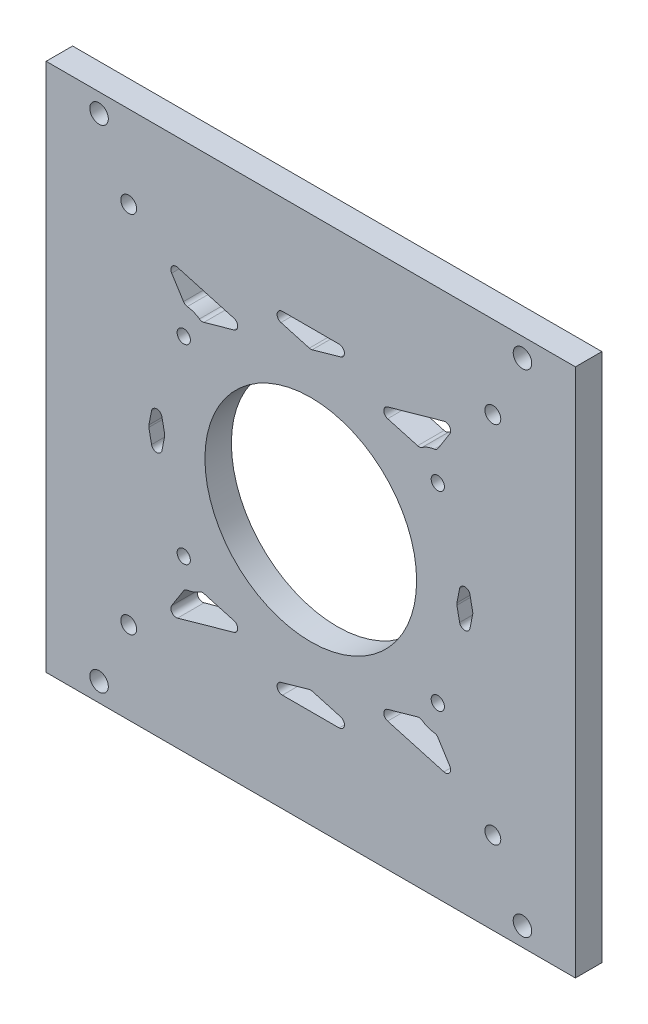
SolidWorks part; units mm, degrees
ref_plane "前视基准面" through (0, 0, 0) normal (0, 0, 1) x (1, 0, 0)
ref_plane "上视基准面" through (0, 0, 0) normal (0, 1, 0) x (1, 0, 0)
ref_plane "右视基准面" through (0, 0, 0) normal (1, 0, 0) x (0, 0, -1)
other "Configuration Table"
sketch "草图1" plane through (0, 0, 0) normal (0, 0, 1) x (1, 0, 0)
  line L1 (0, 0) -> (100, 0)
  line L2 (0, 0) -> (0, 100)
  line L3 (0, 100) -> (100, 100)
  line L4 (100, 0) -> (100, 100)
  line L5 (0, 0) -> (100, 100) construction
  line L6 (0, 100) -> (100, 0) construction
  point P4 (50, 50)
  dimension "D1" = 100
  dimension "D2" = 100
extrude "凸台-拉伸1" add sketch "草图1" along normal blind 5
sketch "草图2" plane through (0, 0, 5) normal (0, 0, 1) x (1, 0, 0)
  line L0 (28.3742, 96.45) -> (104.2073, 96.45) construction
  line L1 (0, 100) -> (100, 100)
  line L2 (0, 100) -> (0, 92.9)
  line L3 (0, 92.9) -> (100, 92.9)
  line L4 (0, 100) -> (0, 0)
  line L5 (0, 0) -> (100, 0)
  line L6 (100, 0) -> (100, 100)
  line L7 (100, 100) -> (0, 100)
  line L8 (0, 100) -> (0, 0)
  line L9 (0, 0) -> (100, 0)
  line L10 (100, 0) -> (100, 100)
  line L11 (100, 100) -> (0, 100)
  line L12 (100, 100) -> (100, 92.9)
  line L13 (0, 100) -> (100, 92.9) construction
  line L14 (0, 92.9) -> (100, 100) construction
  line L15 (0, 0) -> (100, 0)
  line L16 (0, 0) -> (0, 7.1)
  line L17 (0, 7.1) -> (100, 7.1)
  line L18 (100, 0) -> (100, 7.1)
  line L19 (0, 0) -> (100, 7.1) construction
  line L20 (0, 7.1) -> (100, 0) construction
  line L21 (5.1289, 3.55) -> (117.9259, 3.55) construction
  circle A0 centre (10, 96.45) radius 1.75
  circle A1 centre (90, 96.45) radius 1.75
  circle A2 centre (10, 3.55) radius 1.75
  circle A3 centre (90, 3.55) radius 1.75
  point P6 (50, 96.45)
  point P9 (50, 3.55)
  dimension "D4" = 3.5
  dimension "D5" = 3.5
  dimension "D6" = 3.5
  dimension "D7" = 3.5
  dimension "D2" = 7.1
  dimension "D3" = 7.1
  dimension "D8" = 10
  dimension "D9" = 10
  dimension "D10" = 10
  dimension "D11" = 10
  dimension "D1" = 0
extrude "切除-拉伸1" cut sketch "草图2" against normal blind 5 contours A0 | A1 | A2 | A3
sketch "草图3" plane through (0, 0, 5) normal (0, 0, 1) x (1, 0, 0)
  line L0 (100, 0) -> (100, 100) construction
  line L1 (0, 100) -> (100, 100) construction
  line L2 (0, 100) -> (0, 92.9) construction
  line L3 (0, 92.9) -> (100, 92.9) construction
  line L4 (100, 100) -> (100, 92.9) construction
  line L5 (0, 100) -> (100, 92.9) construction
  line L6 (0, 92.9) -> (100, 100) construction
  line L7 (50, 100) -> (50, 0) construction
  line L8 (0, 0) -> (100, 0) construction
  line L9 (0, 0) -> (0, 7.1) construction
  line L10 (0, 7.1) -> (100, 7.1) construction
  line L11 (100, 0) -> (100, 7.1) construction
  line L12 (0, 0) -> (100, 7.1) construction
  line L13 (0, 7.1) -> (100, 0) construction
  line L14 (50, 50) -> (100, 50) construction
  line L15 (26, 68) -> (74, 68) construction
  line L16 (26, 68) -> (26, 32) construction
  line L17 (74, 68) -> (74, 32) construction
  line L18 (26, 32) -> (74, 32) construction
  line L20 (84.4, 15.6) -> (15.6, 15.6) construction
  line L21 (84.4, 15.6) -> (84.4, 84.4) construction
  line L22 (84.4, 84.4) -> (15.6, 84.4) construction
  line L23 (15.6, 15.6) -> (15.6, 84.4) construction
  line L24 (84.4, 15.6) -> (15.6, 84.4) construction
  line L25 (84.4, 84.4) -> (15.6, 15.6) construction
  circle A1 centre (26, 68) radius 1.25
  circle A2 centre (74, 68) radius 1.25
  circle A3 centre (26, 32) radius 1.25
  circle A4 centre (74, 32) radius 1.25
  circle A5 centre (15.6, 84.4) radius 1.5
  circle A6 centre (84.4, 84.4) radius 1.5
  circle A7 centre (84.4, 15.6) radius 1.5
  circle A9 centre (15.6, 15.6) radius 1.5
  circle A10 centre (50, 50) radius 20
  point P4 (50, 96.45)
  point P12 (50, 3.55)
  point P26 (50, 68)
  point P27 (26, 50)
  point P28 (74, 50)
  point P29 (50, 32)
  point P30 (50, 50)
  dimension "D5" = 2.5
  dimension "D6" = 2.5
  dimension "D7" = 2.5
  dimension "D8" = 2.5
  dimension "D11" = 3
  dimension "D12" = 3
  dimension "D13" = 3
  dimension "D14" = 3
  dimension "D15" = 40
  dimension "D1" = 7.1
  dimension "D2" = 7.1
  dimension "D3" = 48
  dimension "D4" = 36
  dimension "D9" = 68.8
  dimension "D10" = 68.8
extrude "切除-拉伸2" cut sketch "草图3" against normal blind 5
sketch "草图4" plane through (0, 0, 5) normal (0, 0, 1) x (1, 0, 0)
  line L0 (15.6, 84.4) -> (84.4, 84.4)
  line L1 (84.4, 84.4) -> (74, 68)
  line L2 (74, 68) -> (74, 32)
  line L3 (74, 32) -> (84.4, 15.6)
  line L4 (0, 100) -> (0, 0)
  line L5 (0, 0) -> (100, 0)
  line L6 (100, 0) -> (100, 100)
  line L7 (100, 100) -> (0, 100)
  line L8 (0, 100) -> (0, 0)
  line L9 (0, 0) -> (100, 0)
  line L10 (100, 0) -> (100, 100)
  line L11 (100, 100) -> (0, 100)
  line L12 (84.4, 15.6) -> (15.6, 15.6)
  line L13 (15.6, 15.6) -> (26, 32)
  line L14 (26, 32) -> (26, 68)
  line L15 (26, 68) -> (15.6, 84.4)
  line L16 (26, 68) -> (74, 68)
  line L17 (50, 50) -> (26, 68)
  line L18 (50, 50) -> (74, 32)
  line L19 (15.6, 84.4) -> (15.6, 15.6)
  line L20 (26, 32) -> (74, 32)
  line L21 (50, 50) -> (26, 32)
  line L22 (50, 50) -> (74, 68)
  line L23 (84.4, 84.4) -> (84.4, 15.6)
  line L24 (26, 68) -> (84.4, 84.4)
  line L25 (15.6, 84.4) -> (74, 68)
  line L26 (26, 68) -> (15.6, 15.6)
  line L27 (26, 32) -> (15.6, 84.4)
  line L28 (26, 32) -> (84.4, 15.6)
  line L29 (74, 32) -> (15.6, 15.6)
  line L30 (74, 32) -> (84.4, 84.4)
  line L31 (74, 68) -> (84.4, 15.6)
  line L32 (15.6, 81.4) -> (84.4, 81.4)
  line L33 (14.7889, 81.5117) -> (73.1889, 65.1117)
  line L34 (26.8111, 65.1117) -> (85.2111, 81.5117)
  line L35 (28.5335, 69.6066) -> (18.1335, 86.0066)
  line L36 (12.6, 84.4) -> (12.6, 15.6)
  line L37 (28.9426, 32.584) -> (18.5426, 84.984)
  line L38 (23.0574, 68.584) -> (12.6574, 16.184)
  line L39 (73.1889, 34.8883) -> (14.7889, 18.4883)
  line L40 (84.4, 18.6) -> (15.6, 18.6)
  line L41 (25.1889, 29.1117) -> (83.5889, 12.7117)
  line L42 (71.4665, 30.3934) -> (81.8665, 13.9934)
  line L43 (18.1335, 13.9934) -> (28.5335, 30.3934)
  line L44 (81.8665, 86.0066) -> (71.4665, 69.6066)
  line L45 (81.4, 84.4) -> (81.4, 15.6)
  line L46 (76.9426, 31.416) -> (87.3426, 83.816)
  line L47 (71.0574, 67.416) -> (81.4574, 15.016)
  line L48 (71, 68) -> (71, 32)
  line L49 (26, 65) -> (74, 65)
  line L50 (29, 32) -> (29, 68)
  line L51 (26, 29) -> (74, 29)
  line L52 (15.6, 87.4) -> (84.4, 87.4)
  line L53 (16.4111, 87.2883) -> (74.8111, 70.8883)
  line L54 (25.1889, 70.8883) -> (83.5889, 87.2883)
  line L55 (23.4665, 66.3934) -> (13.0665, 82.7934)
  line L56 (18.6, 84.4) -> (18.6, 15.6)
  line L57 (23.0574, 31.416) -> (12.6574, 83.816)
  line L58 (28.9426, 67.416) -> (18.5426, 15.016)
  line L59 (74.8111, 29.1117) -> (16.4111, 12.7117)
  line L60 (84.4, 12.6) -> (15.6, 12.6)
  line L61 (26.8111, 34.8883) -> (85.2111, 18.4883)
  line L62 (76.5335, 33.6066) -> (86.9335, 17.2066)
  line L63 (13.0665, 17.2066) -> (23.4665, 33.6066)
  line L64 (86.9335, 82.7934) -> (76.5335, 66.3934)
  line L65 (87.4, 84.4) -> (87.4, 15.6)
  line L66 (71.0574, 32.584) -> (81.4574, 84.984)
  line L67 (76.9426, 68.584) -> (87.3426, 16.184)
  line L68 (77, 68) -> (77, 32)
  line L69 (26, 71) -> (74, 71)
  line L70 (23, 32) -> (23, 68)
  line L71 (26, 35) -> (74, 35)
  circle A0 centre (10, 96.45) radius 1.75 construction
  circle A1 centre (10, 96.45) radius 1.75
  circle A2 centre (15.6, 84.4) radius 5.5
  circle A3 centre (74, 32) radius 1.25
  circle A4 centre (74, 32) radius 1.25
  circle A5 centre (26, 32) radius 1.25
  circle A6 centre (26, 32) radius 1.25
  circle A7 centre (74, 68) radius 1.25
  circle A8 centre (74, 68) radius 1.25
  circle A9 centre (26, 68) radius 1.25
  circle A10 centre (26, 68) radius 1.25
  circle A11 centre (50, 50) radius 20
  circle A12 centre (50, 50) radius 20
  circle A13 centre (15.6, 15.6) radius 1.5
  circle A14 centre (15.6, 15.6) radius 1.5
  circle A15 centre (84.4, 15.6) radius 1.5
  circle A16 centre (84.4, 15.6) radius 1.5
  circle A17 centre (84.4, 84.4) radius 1.5
  circle A18 centre (84.4, 84.4) radius 1.5
  circle A19 centre (15.6, 84.4) radius 1.5
  circle A20 centre (15.6, 84.4) radius 1.5
  circle A21 centre (84.4, 84.4) radius 5.5
  circle A22 centre (74, 68) radius 5.25
  circle A23 centre (26, 68) radius 5.25
  circle A24 centre (50, 50) radius 24
  circle A25 centre (26, 32) radius 5.25
  circle A26 centre (15.6, 15.6) radius 5.5
  circle A27 centre (84.4, 15.6) radius 5.5
  circle A28 centre (74, 32) radius 5.25
  dimension "D1" = 0
  dimension "D2" = 0
  dimension "D3" = 0
  dimension "D4" = 0
  dimension "D5" = 0
  dimension "D6" = 0
  dimension "D7" = 0
  dimension "D8" = 0
  dimension "D9" = 0
  dimension "D10" = 0
  dimension "D11" = 4
  dimension "D12" = 3
  dimension "D13" = 3
extrude "切除-拉伸3" cut sketch "草图4" against normal blind 5 contours L53 L54 L32 | A23 L54 L33 L35 | A22 L44 L34 L53 | L41 L59 L40 | A25 L43 L39 L41 | A28 L59 L61 L42 | L57 L26 L27 L38 | L67 L30 L31 L46
fillet "圆角27" radius 1 30 edges at (38.9038, 74.7397, 2.5) (29.3369, 72.0531, 2.5) (26.2262, 73.2451, 2.5) (61.0962, 74.7397, 2.5) (77.6738, 79.3951, 2.5) (73.7738, 73.2451, 2.5) (70.6631, 72.0531, 2.5) (38.9038, 25.2603, 2.5) (22.3262, 20.6049, 2.5) (26.2262, 26.7549, 2.5) (29.3369, 27.9469, 2.5) (37.3791, 18.6, 2.5) (50, 22.1442, 2.5) (62.6209, 18.6, 2.5) (79.1018, 42.2949, 2.5) (77.5725, 50, 2.5) (79.1018, 57.7051, 2.5) (80.631, 50, 2.5) (20.8982, 57.7051, 2.5) (22.4275, 50, 2.5) (20.8982, 42.2949, 2.5) (19.369, 50, 2.5) (77.6738, 20.6049, 2.5) (61.0962, 25.2603, 2.5) (70.6631, 27.9469, 2.5) (73.7738, 26.7549, 2.5) (37.3791, 81.4, 2.5) (62.6209, 81.4, 2.5) (50, 77.8558, 2.5) (22.3262, 79.3951, 2.5)
